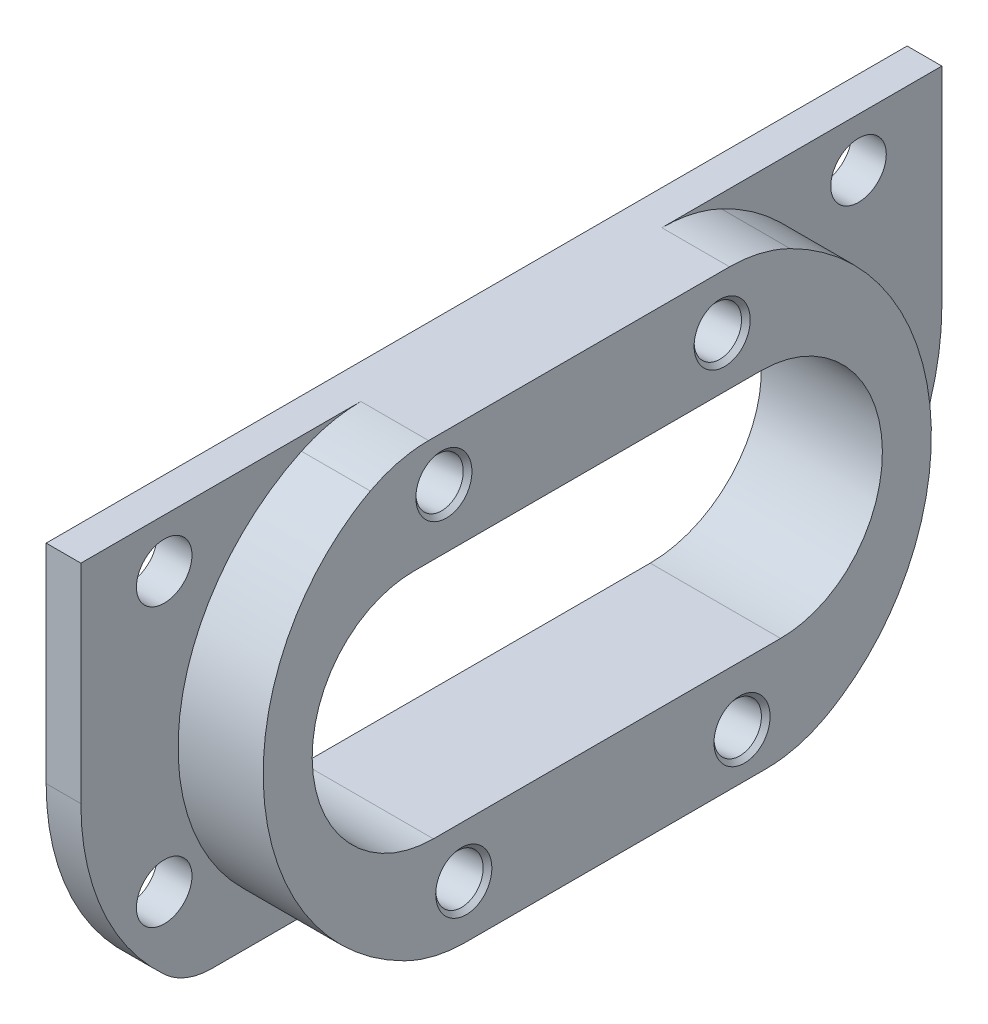
SolidWorks part; units mm, degrees
ref_plane "Płaszczyzna przednia" through (0, 0, 0) normal (0, 0, 1) x (1, 0, 0)
ref_plane "Płaszczyzna górna" through (0, 0, 0) normal (0, 1, 0) x (1, 0, 0)
ref_plane "Płaszczyzna prawa" through (0, 0, 0) normal (1, 0, 0) x (0, 0, -1)
sketch "Szkic1" plane through (0, 0, 0) normal (1, 0, 0) x (0, 0, -1)
  line L0 (-25, -16) -> (25, -16)
  line L1 (25, 16) -> (-25, 16)
  line L2 (-43.1384, -30) -> (43.1384, -30)
  line L3 (-62, 0) -> (62, 0) construction
  line L4 (-62, 30) -> (62, 30)
  line L5 (62, 0) -> (62, 30)
  line L6 (-62, 30) -> (-62, 0)
  line L7 (0, 0) -> (0, 30) construction
  arc A0 (-25, 16) -> (-25, -16) centre (-25, 0) ccw
  arc A1 (25, -16) -> (25, 16) centre (25, 0) ccw
  arc A2 (43.1384, -30) -> (49.8563, -27.4074) centre (43.1384, -20) ccw
  arc A3 (-49.8563, -27.4074) -> (-43.1384, -30) centre (-43.1384, -20) ccw
  arc A6 (49.8563, -27.4074) -> (62, 0) centre (25, 0) ccw
  arc A7 (-62, 0) -> (-49.8563, -27.4074) centre (-25, 0) ccw
  circle A8 centre (-50, 23) radius 4
  circle A9 centre (50, 23) radius 4
  circle A10 centre (50, -17) radius 4
  circle A11 centre (-50, -17) radius 4
  dimension "D2" = 16
  dimension "D3" = 10
  dimension "D4" = 7
  dimension "D5" = 37
  dimension "D10" = 8
  dimension "D1" = 50
  dimension "D6" = 43.1384
  dimension "D7" = 50
  dimension "D8" = 2
  dimension "D9" = 2
extrude "Dodanie-wyciągnięcie1" add sketch "Szkic1" along normal blind 20
sketch "Szkic2" plane through (20, 0, 0) normal (1, 0, 0) x (0, 0, -1)
  line L0 (-25, -16) -> (25, -16) construction
  line L1 (25, 16) -> (-25, 16) construction
  line L2 (-25, -16) -> (25, -16)
  line L3 (25, 16) -> (-25, 16)
  line L6 (21.6718, 30) -> (-21.6718, 30)
  line L7 (-21.6718, -30) -> (21.6718, -30)
  line L8 (0, 0) -> (0, 16) construction
  arc A0 (25, -16) -> (25, 16) centre (25, 0) ccw construction
  arc A1 (-25, 16) -> (-25, -16) centre (-25, 0) ccw construction
  arc A2 (25, -16) -> (25, 16) centre (25, 0) ccw
  arc A3 (-25, 16) -> (-25, -16) centre (-25, 0) ccw
  arc A6 (-30.2337, -28.0747) -> (-30.2337, 28.0747) centre (-16.9348, 0) cw
  arc A7 (30.2337, -28.0747) -> (30.2337, 28.0747) centre (16.9348, 0) ccw
  arc A8 (-30.2337, -28.0747) -> (-21.6718, -30) centre (-21.6718, -10) ccw
  arc A9 (21.6718, -30) -> (30.2337, -28.0747) centre (21.6718, -10) ccw
  arc A10 (30.2337, 28.0747) -> (21.6718, 30) centre (21.6718, 10) ccw
  arc A11 (-21.6718, 30) -> (-30.2337, 28.0747) centre (-21.6718, 10) ccw
  point P4 (-25, 0)
  point P5 (-25, 23)
  point P8 (-25, -23)
  point P9 (25, -23)
  point P10 (25, 0)
  point P11 (25, 23)
  point P23 (-25, -30)
  point P26 (25, -30)
  point P29 (25, 30)
  point P32 (-25, 30)
  dimension "D1" = 20
  dimension "D2" = 20
  dimension "D3" = 20
  dimension "D4" = 20
extrude "Wytnij-wyciągnięcie1" cut sketch "Szkic2" against normal blind 15 flip side to cut
sketch "Szkic3" plane through (0, 0, -62) normal (0, 0, -1) x (-1, 0, 0)
  line L2 (-14.7507, 30) -> (-20, 30)
  line L4 (-5, 0) -> (-20, 0) construction
  line L8 (-20, -30) -> (-20, 30)
  line L9 (-20, -30) -> (-14.7507, 30)
extrude "Wytnij-wyciągnięcie2" cut sketch "Szkic3" against normal through all both and the other way through all
sketch "Szkic9" plane through (17.5073, -1.5086, 0) normal (0.9962, 0.0872, 0) x (0, 0, -1)
  line L0 (0, 1.5144) -> (-41.9451, 2.6127) construction
  line L1 (0, 0) -> (0, 22.9605) construction
  line L7 (0, 0) -> (0, -18.3021) construction
  point P4 (-20, 25.5461)
  point P8 (19.9863, 24.4991)
  point P10 (18.756, -22.4848)
  point P12 (-21.2303, -21.4378)
  dimension "D2" = 23.5
  dimension "D3" = 20
  dimension "D6" = 88.5
  dimension "D4" = 2
  dimension "D5" = 2
hole_wizard "Otwór gwintowany M81" positions "Szkic 3D1" profile "Szkic11" tap size "M8" standard "ISO"
sketch3d "Szkic 3D1"
  point P25 (15.2808, 23.9403, 20)
  point P28 (15.3721, 22.8972, -19.9863)
  point P31 (19.3757, -22.8648, 21.2303)
  point P34 (19.467, -23.9079, -18.756)
sketch "Szkic11" plane through (15.2808, 23.9403, 20) normal (0, 0, 1) x (-0.0872, 0.9962, 0)
  line L0 (0, 0) -> (0, 15)
  line L1 (0, 15) -> (3.4, 12.9571)
  line L2 (3.4, 12.9571) -> (3.4, 0.625)
  line L3 (3.4, 0.625) -> (4.025, 0)
  line L5 (4.025, 0) -> (0, 0)
  line L6 (-3.4, 0.625) -> (-4.025, 0) construction
  line L10 (0, 15) -> (-3.4, 12.9571) construction
  line L11 (0, -6.35) -> (0, 107.95) construction
  dimension "Średnica wiertła gwintu" = 6.8
  dimension "Głębokość otworu gwintowanego" = 15
  dimension "Średnica zewnętrznego pogłębienia stożkowego" = 8.05
  dimension "Kąt zewnętrznego pogłębienia stożkowego" = 90
  dimension "Kąt wiertła" = 118
cosmetic thread "Gwint otworu1" parameters "D1"=12, "D2"=8
cosmetic thread "Gwint otworu2" parameters "D1"=12, "D2"=8
cosmetic thread "Gwint otworu3" parameters "D1"=12, "D2"=8
cosmetic thread "Gwint otworu4" parameters "D1"=12, "D2"=8
